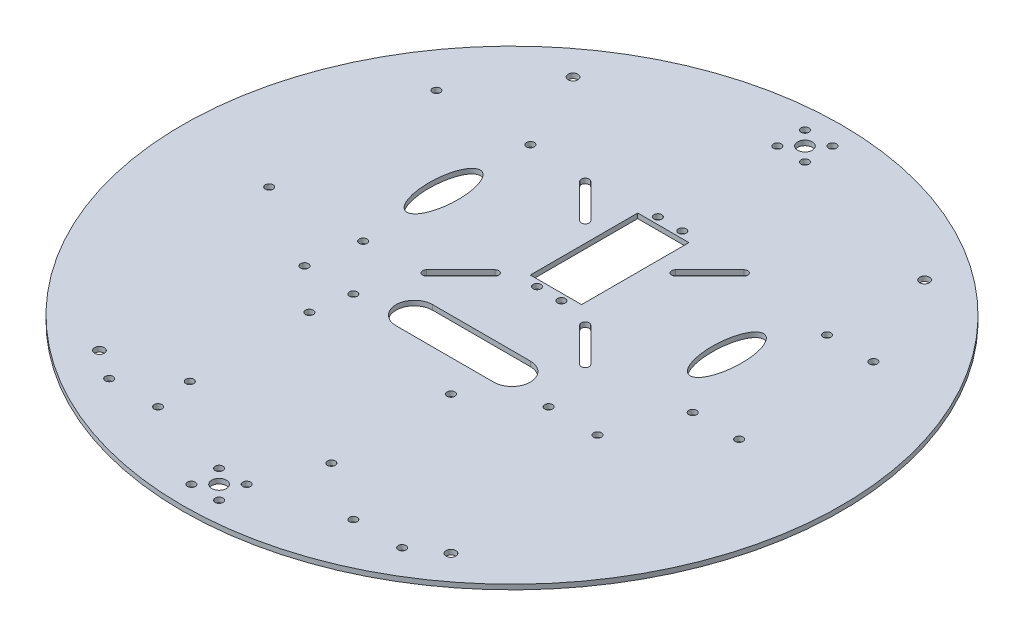
SolidWorks part; units mm, degrees
ref_plane "前视基准面" through (0, 0, 0) normal (0, 0, 1) x (1, 0, 0)
ref_plane "上视基准面" through (0, 0, 0) normal (0, 1, 0) x (1, 0, 0)
ref_plane "右视基准面" through (0, 0, 0) normal (1, 0, 0) x (0, 0, -1)
sketch "草图1" plane through (0, 0, 0) normal (0, 1, 0) x (1, 0, 0)
  line L0 (0, 135) -> (0, -135) construction
  line L1 (-80, 80) -> (80, 80) construction
  line L2 (-80, 80) -> (-80, -80) construction
  line L3 (-80, -80) -> (80, -80) construction
  line L4 (80, 80) -> (80, -80) construction
  line L5 (-80, 80) -> (80, -80) construction
  line L6 (-80, -80) -> (80, 80) construction
  line L7 (-135, 0) -> (135, 0) construction
  line L9 (-30, 60) -> (30, 60) construction
  line L10 (-30, 60) -> (-30, 0) construction
  line L11 (-30, 0) -> (30, 0) construction
  line L12 (30, 60) -> (30, 0) construction
  line L13 (-30, 60) -> (30, 0) construction
  line L14 (-30, 0) -> (30, 60) construction
  circle A0 centre (0, 0) radius 135
  point P17 (0, 0)
  point P19 (0, 30)
  dimension "D1" = 270
  dimension "D2" = 160
  dimension "D3" = 160
  dimension "D5" = 30
  dimension "D6" = 60
  dimension "D7" = 60
extrude "凸台-拉伸1" add sketch "草图1" along normal blind 2
sketch "云台安装孔" plane through (0, 2, 0) normal (0, 1, 0) x (1, 0, 0)
  line L0 (0, 135) -> (0, -135) construction
  line L1 (-135, 0) -> (135, 0) construction
  line L3 (-18.5, 48.5) -> (18.5, 48.5) construction
  line L4 (-18.5, 48.5) -> (-18.5, 11.5) construction
  line L5 (-18.5, 11.5) -> (18.5, 11.5) construction
  line L6 (18.5, 48.5) -> (18.5, 11.5) construction
  line L7 (-18.5, 48.5) -> (18.5, 11.5) construction
  line L8 (-18.5, 11.5) -> (18.5, 48.5) construction
  line L9 (-62.9961, -18.6558) -> (62.9961, -18.6558) construction
  line L10 (-62.9961, -18.6558) -> (-62.9961, -86.2012) construction
  line L11 (-62.9961, -86.2012) -> (62.9961, -86.2012) construction
  line L12 (62.9961, -18.6558) -> (62.9961, -86.2012) construction
  line L13 (-62.9961, -18.6558) -> (62.9961, -86.2012) construction
  line L14 (-62.9961, -86.2012) -> (62.9961, -18.6558) construction
  line L15 (-10.5, 62) -> (10.5, 62)
  line L16 (-10.5, 62) -> (-10.5, 18)
  line L17 (-10.5, 18) -> (10.5, 18)
  line L18 (10.5, 62) -> (10.5, 18)
  line L19 (-10.5, 62) -> (10.5, 18) construction
  line L20 (-10.5, 18) -> (10.5, 62) construction
  line L21 (-5, 64.75) -> (5, 64.75) construction
  line L22 (-5, 64.75) -> (-5, 15.25) construction
  line L23 (-5, 15.25) -> (5, 15.25) construction
  line L24 (5, 64.75) -> (5, 15.25) construction
  line L25 (-5, 64.75) -> (5, 15.25) construction
  line L26 (-5, 15.25) -> (5, 64.75) construction
  line L27 (-38.5, 68.5) -> (38.5, 68.5) construction
  line L28 (-38.5, 68.5) -> (-38.5, -8.5) construction
  line L29 (-38.5, -8.5) -> (38.5, -8.5) construction
  line L30 (38.5, 68.5) -> (38.5, -8.5) construction
  line L31 (-38.5, 68.5) -> (38.5, -8.5) construction
  line L32 (-38.5, -8.5) -> (38.5, 68.5) construction
  circle A0 centre (0, 0) radius 135 construction
  circle A1 centre (-5, 64.75) radius 1.6
  circle A2 centre (5, 64.75) radius 1.6
  circle A3 centre (-5, 15.25) radius 1.6
  circle A4 centre (5, 15.25) radius 1.6
  circle A5 centre (18.5, 48.5) radius 1.6
  circle A6 centre (18.5, 11.5) radius 1.6
  circle A7 centre (-18.5, 11.5) radius 1.6
  circle A8 centre (-18.5, 48.5) radius 1.6
  point P3 (0, 30)
  point P8 (0, 30)
  point P13 (0, -52.4285)
  point P18 (0, 40)
  point P23 (0, 40)
  point P50 (0, 30)
  dimension "D3" = 21
  dimension "D8" = 3.2
  dimension "D9" = 3.2
  dimension "D10" = 3.2
  dimension "D11" = 3.2
  dimension "D12" = 3.2
  dimension "D13" = 3.2
  dimension "D1" = 37
  dimension "D2" = 37
  dimension "D4" = 44
  dimension "D5" = 10
  dimension "D6" = 10
  dimension "D7" = 49.5
  dimension "D14" = 30
  dimension "D15" = 77
  dimension "D16" = 77
extrude "切除-拉伸1" cut sketch "云台安装孔" against normal blind 10
sketch "扩展板安装孔" plane through (0, 2, 0) normal (0, 1, 0) x (1, 0, 0)
  line L0 (0, 135) -> (0, -135) construction
  line L1 (15.5, -40.5) -> (15.5, -89.5) construction
  line L2 (-60, -25) -> (60, -25) construction
  line L3 (-60, -25) -> (-60, -105) construction
  line L4 (-60, -105) -> (60, -105) construction
  line L5 (60, -25) -> (60, -105) construction
  line L6 (-60, -25) -> (60, -105) construction
  line L7 (-60, -105) -> (60, -25) construction
  line L8 (-40, -25) -> (40, -25) construction
  line L9 (-40, -25) -> (-40, -105) construction
  line L10 (-40, -105) -> (40, -105) construction
  line L11 (40, -25) -> (40, -105) construction
  line L12 (-40, -25) -> (40, -105) construction
  line L13 (-40, -105) -> (40, -25) construction
  line L14 (-42.5, -40.5) -> (42.5, -40.5) construction
  line L15 (-42.5, -40.5) -> (-42.5, -89.5) construction
  line L16 (-42.5, -89.5) -> (42.5, -89.5) construction
  line L17 (42.5, -40.5) -> (42.5, -89.5) construction
  line L18 (-42.5, -40.5) -> (42.5, -89.5) construction
  line L19 (-42.5, -89.5) -> (42.5, -40.5) construction
  circle A0 centre (0, 0) radius 135 construction
  circle A1 centre (-60, -25) radius 1.6
  circle A2 centre (-40, -25) radius 1.6
  circle A3 centre (40, -25) radius 1.6
  circle A4 centre (60, -25) radius 1.6
  circle A5 centre (60, -105) radius 1.6
  circle A6 centre (40, -105) radius 1.6
  circle A7 centre (-40, -105) radius 1.6
  circle A8 centre (-60, -105) radius 1.6
  circle A9 centre (-42.5, -89.5) radius 1.6
  circle A12 centre (-42.5, -40.5) radius 1.6
  circle A13 centre (15.5, -40.5) radius 1.6
  circle A14 centre (15.5, -89.5) radius 1.6
  point P5 (0, -65)
  point P10 (0, -65)
  point P15 (0, -65)
  dimension "D7" = 65
  dimension "D1" = 120
  dimension "D2" = 80
  dimension "D3" = 80
  dimension "D4" = 85
  dimension "D5" = 49
  dimension "D6" = 58
extrude "切除-拉伸2" cut sketch "扩展板安装孔" against normal blind 10
sketch "草图4" plane through (0, 2, 0) normal (0, 1, 0) x (1, 0, 0)
  line L0 (0, 135) -> (0, -135) construction
  line L1 (-135, 0) -> (135, 0) construction
  line L2 (-20, -12.5) -> (20, -12.5)
  line L3 (-20, -12.5) -> (-20, -27.5) construction
  line L4 (-20, -27.5) -> (20, -27.5)
  line L5 (20, -12.5) -> (20, -27.5) construction
  line L6 (-20, -12.5) -> (20, -27.5) construction
  line L7 (-20, -27.5) -> (20, -12.5) construction
  line L8 (-72, 97) -> (72, 97) construction
  line L9 (-72, 97) -> (-72, -97) construction
  line L10 (-72, -97) -> (72, -97) construction
  line L11 (72, 97) -> (72, -97) construction
  line L12 (-72, 97) -> (72, -97) construction
  line L13 (-72, -97) -> (72, 97) construction
  circle A0 centre (0, 0) radius 135 construction
  arc A1 (-20, -12.5) -> (-20, -27.5) centre (-20, -20) ccw
  arc A2 (20, -12.5) -> (20, -27.5) centre (20, -20) cw
  circle A3 centre (-72, 97) radius 2
  circle A4 centre (72, 97) radius 2
  circle A5 centre (72, -97) radius 2
  circle A6 centre (-72, -97) radius 2
  circle A7 centre (0, -120) radius 3
  circle A8 centre (0, 120) radius 8 construction
  circle A9 centre (-5.6569, -125.6569) radius 1.6
  circle A10 centre (-5.6569, -114.3431) radius 1.6
  circle A11 centre (5.6569, -114.3431) radius 1.6
  circle A12 centre (5.6569, -125.6569) radius 1.6
  circle A13 centre (5.6569, 125.6569) radius 1.6
  circle A14 centre (5.6569, 114.3431) radius 1.6
  circle A15 centre (-5.6569, 114.3431) radius 1.6
  circle A16 centre (-5.6569, 125.6569) radius 1.6
  circle A17 centre (0, -120) radius 8 construction
  circle A18 centre (0, 120) radius 3
  point P5 (0, -20)
  point P12 (0, 0)
  point P41 (0, -120)
  point P50 (0, 120)
  dimension "D5" = 120
  dimension "D6" = 4
  dimension "D7" = 4
  dimension "D8" = 4
  dimension "D9" = 4
  dimension "D12" = 4
  dimension "D10" = 16
  dimension "D11" = 4
  dimension "D14" = 6
  dimension "D1" = 15
  dimension "D2" = 40
  dimension "D3" = 144
  dimension "D4" = 194
  dimension "D13" = 20
extrude "切除-拉伸3" cut sketch "草图4" against normal blind 10
sketch "草图5" plane through (0, 2, 0) normal (0, 1, 0) x (1, 0, 0)
  line L0 (-31.3686, 63.6314) -> (-17.3686, 49.6314)
  line L1 (-10.5, 62) -> (-10.5, 18) construction
  line L2 (-33.6314, 61.3686) -> (-19.6314, 47.3686)
  line L3 (-32.5, 62.5) -> (32.5, 62.5) construction
  line L4 (-32.5, 62.5) -> (-32.5, -2.5) construction
  line L5 (-32.5, -2.5) -> (32.5, -2.5) construction
  line L6 (32.5, 62.5) -> (32.5, -2.5) construction
  line L7 (-32.5, 62.5) -> (32.5, -2.5) construction
  line L8 (-32.5, -2.5) -> (32.5, 62.5) construction
  line L9 (33.6314, 61.3686) -> (19.6314, 47.3686)
  line L10 (31.3686, 63.6314) -> (17.3686, 49.6314)
  line L11 (31.3686, -3.6314) -> (17.3686, 10.3686)
  line L12 (33.6314, -1.3686) -> (19.6314, 12.6314)
  line L13 (-33.6314, -1.3686) -> (-19.6314, 12.6314)
  line L14 (-31.3686, -3.6314) -> (-17.3686, 10.3686)
  arc A0 (33.6314, 61.3686) -> (31.3686, 63.6314) centre (32.5, 62.5) ccw
  arc A1 (-19.6314, 47.3686) -> (-17.3686, 49.6314) centre (-18.5, 48.5) ccw
  arc A2 (-31.3686, 63.6314) -> (-33.6314, 61.3686) centre (-32.5, 62.5) ccw
  arc A3 (17.3686, 49.6314) -> (19.6314, 47.3686) centre (18.5, 48.5) ccw
  arc A4 (31.3686, -3.6314) -> (33.6314, -1.3686) centre (32.5, -2.5) ccw
  arc A5 (19.6314, 12.6314) -> (17.3686, 10.3686) centre (18.5, 11.5) ccw
  arc A6 (-33.6314, -1.3686) -> (-31.3686, -3.6314) centre (-32.5, -2.5) ccw
  arc A7 (-17.3686, 10.3686) -> (-19.6314, 12.6314) centre (-18.5, 11.5) ccw
  point P5 (0, 30)
  point P35 (0, 30)
  dimension "D4" = 3.2
  dimension "D1" = 30
  dimension "D2" = 10.5
  dimension "D3" = 65
  dimension "D5" = 1.6
  dimension "D6" = 4
extrude "切除-拉伸4" cut sketch "草图5" against normal blind 10
sketch "草图6" plane through (0, 2, 0) normal (0, 1, 0) x (1, 0, 0)
  line L0 (33.6314, -3.6314) -> (33.6314, 63.6314) construction
  line L1 (33.6314, 30) -> (118.3005, 30) construction
  line L2 (0, 120) -> (0, -27.5) construction
  line L3 (-20, -27.5) -> (20, -27.5) construction
  line L4 (-33.6314, -3.6314) -> (-33.6314, 63.6314) construction
  line L5 (71.5372, 2.5) -> (90.5372, 2.5) construction
  line L6 (71.5372, 2.5) -> (71.5372, 57.5) construction
  line L7 (71.5372, 57.5) -> (90.5372, 57.5) construction
  line L8 (90.5372, 2.5) -> (90.5372, 57.5) construction
  line L9 (71.5372, 2.5) -> (90.5372, 57.5) construction
  line L10 (71.5372, 57.5) -> (90.5372, 2.5) construction
  line L11 (-33.6314, 30) -> (-118.3005, 30) construction
  line L14 (-95.216, -4.25) -> (-56.716, -4.25) construction
  line L15 (-95.216, -4.25) -> (-95.216, 64.25) construction
  line L16 (-95.216, 64.25) -> (-56.716, 64.25) construction
  line L17 (-56.716, -4.25) -> (-56.716, 64.25) construction
  line L18 (-95.216, -4.25) -> (-56.716, 64.25) construction
  line L19 (-95.216, 64.25) -> (-56.716, -4.25) construction
  arc A0 (31.3686, -3.6314) -> (33.6314, -1.3686) centre (32.5, -2.5) ccw construction
  arc A1 (33.6314, 61.3686) -> (31.3686, 63.6314) centre (32.5, 62.5) ccw construction
  circle A2 centre (71.5372, 2.5) radius 1.6
  circle A3 centre (90.5372, 2.5) radius 1.6
  circle A4 centre (90.5372, 57.5) radius 1.6
  circle A5 centre (71.5372, 57.5) radius 1.6
  circle A6 centre (-95.216, -4.25) radius 1.6
  circle A7 centre (-56.716, -4.25) radius 1.6
  circle A8 centre (-95.216, 64.25) radius 1.6
  circle A9 centre (-56.716, 64.25) radius 1.6
  ellipse E0 centre (-58.0311, 30) end of major axis (-58.0311, 15) minor radius 6
  ellipse E1 centre (58.0311, 30) end of major axis (58.0311, 45) minor radius 6
  point P15 (81.0372, 30)
  point P49 (-75.966, 30)
  dimension "D3" = 6
  dimension "D7" = 3.2
  dimension "D1" = 19
  dimension "D2" = 55
  dimension "D4" = 15
  dimension "D5" = 38.5
  dimension "D6" = 68.5
extrude "切除-拉伸7" cut sketch "草图6" against normal blind 10
